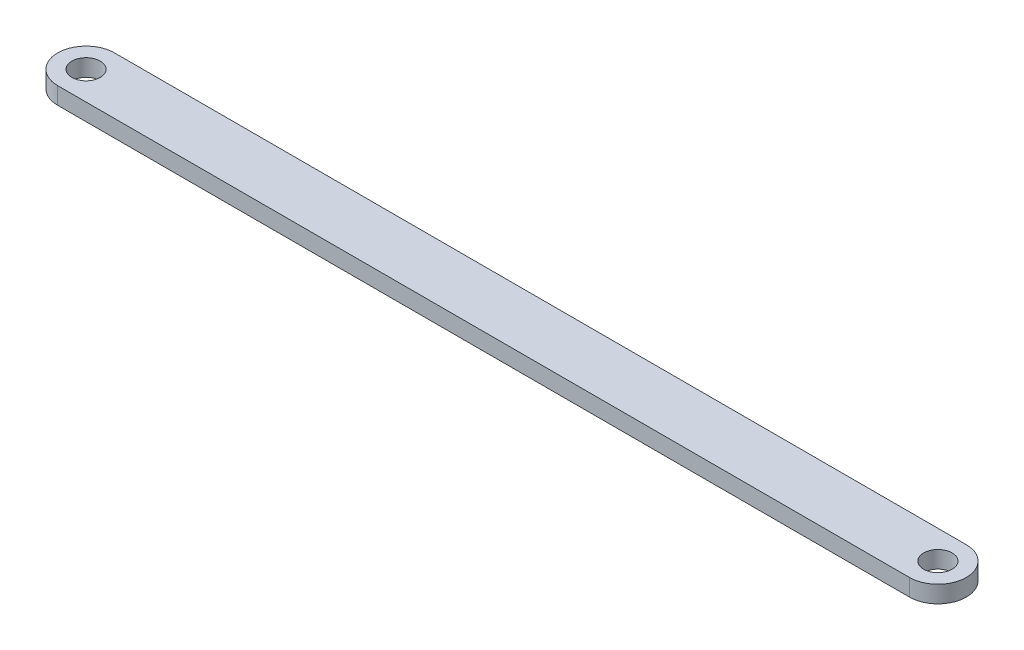
SolidWorks part; units mm, degrees
ref_plane "Front Plane" through (0, 0, 0) normal (0, 0, 1) x (1, 0, 0)
ref_plane "Top Plane" through (0, 0, 0) normal (0, 1, 0) x (1, 0, 0)
ref_plane "Right Plane" through (0, 0, 0) normal (1, 0, 0) x (0, 0, -1)
sketch "Sketch1" plane through (0, 0, 0) normal (0, 1, 0) x (1, 0, 0)
  line L0 (0, 0) -> (150, 0) construction
  line L1 (0, 5) -> (150, 5)
  line L2 (0, -5) -> (150, -5)
  arc A0 (0, 5) -> (0, -5) centre (0, 0) ccw
  arc A1 (150, -5) -> (150, 5) centre (150, 0) ccw
  circle A2 centre (0, 0) radius 2.5
  circle A3 centre (150, 0) radius 2.5
  point P3 (75, 0)
  dimension "D2" = 5
  dimension "D3" = 5
  dimension "D4" = 5
  dimension "D1" = 150
extrude "Boss-Extrude1" add sketch "Sketch1" along normal blind 3
